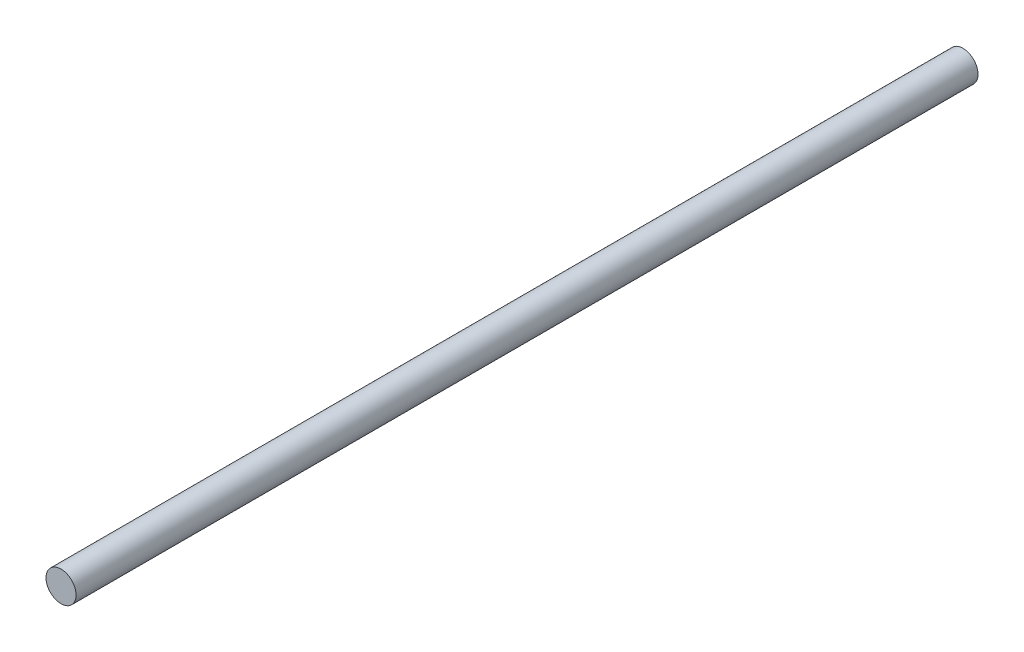
SolidWorks part; units mm, degrees
ref_plane "Front Plane" through (0, 0, 0) normal (0, 0, 1) x (1, 0, 0)
ref_plane "Top Plane" through (0, 0, 0) normal (0, 1, 0) x (1, 0, 0)
ref_plane "Right Plane" through (0, 0, 0) normal (1, 0, 0) x (0, 0, -1)
sketch "Sketch1" plane through (0, 0, 0) normal (0, 0, 1) x (1, 0, 0)
  circle A0 centre (0, 0) radius 1.5
  dimension "D1" = 3
extrude "Boss-Extrude1" add sketch "Sketch1" along normal blind 90
